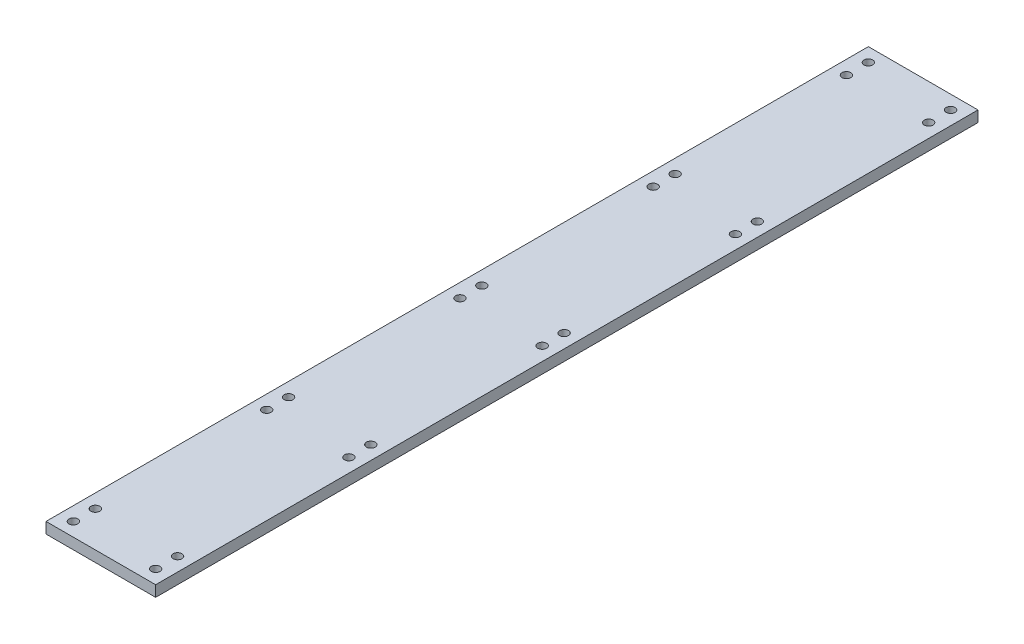
SolidWorks part; units mm, degrees
ref_plane "前视基准面" through (0, 0, 0) normal (0, 0, 1) x (1, 0, 0)
ref_plane "上视基准面" through (0, 0, 0) normal (0, 1, 0) x (1, 0, 0)
ref_plane "右视基准面" through (0, 0, 0) normal (1, 0, 0) x (0, 0, -1)
sketch "草图1" plane through (0, 0, 0) normal (0, 1, 0) x (1, 0, 0)
  line L1 (-20, -150) -> (20, -150)
  line L2 (-20, -150) -> (-20, 150)
  line L3 (-20, 150) -> (20, 150)
  line L4 (20, -150) -> (20, 150)
  line L5 (-20, -150) -> (20, 150) construction
  line L6 (-20, 150) -> (20, -150) construction
  circle A0 centre (-15, 145) radius 1.6
  circle A1 centre (-15, 137) radius 1.6
  circle A2 centre (15, 145) radius 1.6
  circle A3 centre (15, 137) radius 1.6
  circle A4 centre (15, 74.5) radius 1.6
  circle A5 centre (15, 66.5) radius 1.6
  circle A6 centre (15, 4) radius 1.6
  circle A7 centre (15, -4) radius 1.6
  circle A8 centre (15, -66.5) radius 1.6
  circle A9 centre (15, -74.5) radius 1.6
  circle A10 centre (15, -137) radius 1.6
  circle A11 centre (15, -145) radius 1.6
  circle A12 centre (-15, 74.5) radius 1.6
  circle A13 centre (-15, 66.5) radius 1.6
  circle A14 centre (-15, 4) radius 1.6
  circle A15 centre (-15, -4) radius 1.6
  circle A16 centre (-15, -66.5) radius 1.6
  circle A17 centre (-15, -74.5) radius 1.6
  circle A18 centre (-15, -137) radius 1.6
  circle A19 centre (-15, -145) radius 1.6
  point P0 (0, 0)
  dimension "D3" = 8
  dimension "D4" = 3.2
  dimension "D5" = 5
  dimension "D6" = 5
  dimension "D9" = 5
  dimension "D10" = 62.5
  dimension "D11" = 5
  dimension "D1" = 300
  dimension "D2" = 40
  dimension "D7" = 2
  dimension "D8" = 5
extrude "凸台-拉伸1" add sketch "草图1" along normal blind 4
